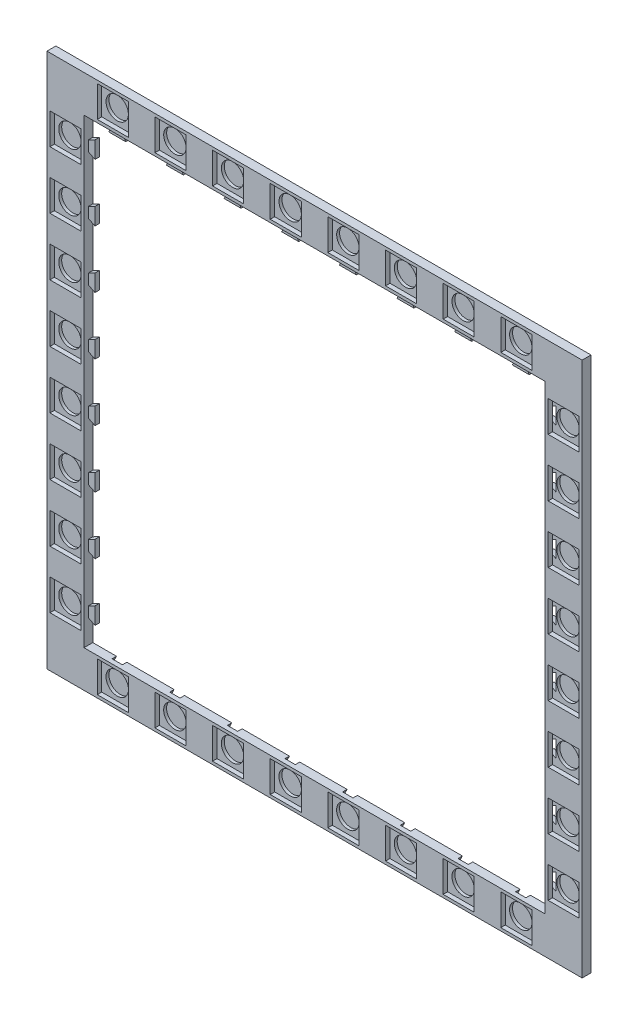
SolidWorks part; units mm, degrees
ref_plane "Front Plane" through (0, 0, 0) normal (1, 0, 0) x (0, 1, 0)
ref_plane "Top Plane" through (0, 0, 0) normal (0, 0, 1) x (0, 1, 0)
ref_plane "Right Plane" through (0, 0, 0) normal (0, 1, 0) x (-1, 0, 0)
sketch "Sketch1" plane through (0, 0, 0) normal (0, 0, 1) x (0, 1, 0)
  line L0 (150.3197, -166.5401) -> (150.3197, -150.5401)
  line L1 (150.3197, 12.4599) -> (150.3197, 44.4599)
  line L2 (154.7904, 81.2211) -> (154.7904, 92.6987)
  line L3 (150.3197, 129.4599) -> (150.3197, 145.4599)
  line L4 (150.3197, -111.5401) -> (154.7904, -113.7789)
  line L5 (154.7904, 14.6987) -> (150.3197, 12.4599)
  line L6 (154.7904, -102.3013) -> (150.3197, -104.5401)
  line L7 (150.3197, -72.5401) -> (154.7904, -74.7789)
  line L8 (150.3197, -150.5401) -> (154.7904, -152.7789)
  line L9 (150.3197, -65.5401) -> (150.3197, -33.5401)
  line L10 (154.7904, -141.3013) -> (150.3197, -143.5401)
  line L11 (154.7904, -35.7789) -> (154.7904, -24.3013)
  line L12 (154.7904, 42.2211) -> (154.7904, 53.6987)
  line L13 (150.3197, 83.4599) -> (154.7904, 81.2211)
  line L14 (154.7904, 3.2211) -> (154.7904, 14.6987)
  line L15 (154.7904, 131.6987) -> (150.3197, 129.4599)
  line L16 (150.3197, 5.4599) -> (154.7904, 3.2211)
  line L17 (150.3197, 122.4599) -> (154.7904, 120.2211)
  line L18 (154.7904, -113.7789) -> (154.7904, -102.3013)
  line L19 (154.7904, 53.6987) -> (150.3197, 51.4599)
  line L20 (150.3197, -104.5401) -> (150.3197, -72.5401)
  line L21 (154.7904, -24.3013) -> (150.3197, -26.5401)
  line L22 (150.3197, 90.4599) -> (150.3197, 122.4599)
  line L23 (154.7904, -63.3013) -> (150.3197, -65.5401)
  line L24 (154.7904, -152.7789) -> (154.7904, -141.3013)
  line L25 (150.3197, -33.5401) -> (154.7904, -35.7789)
  line L26 (154.7904, -74.7789) -> (154.7904, -63.3013)
  line L27 (150.3197, -26.5401) -> (150.3197, 5.4599)
  line L28 (150.3197, 44.4599) -> (154.7904, 42.2211)
  line L29 (154.7904, 120.2211) -> (154.7904, 131.6987)
  line L30 (150.3197, -143.5401) -> (150.3197, -111.5401)
  line L31 (150.3197, 51.4599) -> (150.3197, 83.4599)
  line L32 (154.7904, 92.6987) -> (150.3197, 90.4599)
  line L33 (-161.6803, -150.5401) -> (-157.2096, -152.7789)
  line L34 (-157.2096, -102.3013) -> (-161.6803, -104.5401)
  line L35 (-161.6803, -166.5401) -> (-161.6803, -150.5401)
  line L36 (-157.2096, -35.7789) -> (-157.2096, -24.3013)
  line L37 (-161.6803, 51.4599) -> (-161.6803, 83.4599)
  line L38 (-157.2096, -24.3013) -> (-161.6803, -26.5401)
  line L39 (-157.2096, 42.2211) -> (-157.2096, 53.6987)
  line L40 (-157.2096, 120.2211) -> (-157.2096, 131.6987)
  line L41 (-161.6803, 90.4599) -> (-161.6803, 122.4599)
  line L42 (-157.2096, -141.3013) -> (-161.6803, -143.5401)
  line L43 (-161.6803, 5.4599) -> (-157.2096, 3.2211)
  line L44 (-157.2096, -113.7789) -> (-157.2096, -102.3013)
  line L45 (-157.2096, -74.7789) -> (-157.2096, -63.3013)
  line L46 (-157.2096, 14.6987) -> (-161.6803, 12.4599)
  line L47 (-161.6803, -65.5401) -> (-161.6803, -33.5401)
  line L48 (-157.2096, 53.6987) -> (-161.6803, 51.4599)
  line L49 (-157.2096, 81.2211) -> (-157.2096, 92.6987)
  line L50 (-157.2096, -152.7789) -> (-157.2096, -141.3013)
  line L51 (-161.6803, -111.5401) -> (-157.2096, -113.7789)
  line L52 (-161.6803, -33.5401) -> (-157.2096, -35.7789)
  line L53 (-161.6803, 129.4599) -> (-161.6803, 145.4599)
  line L54 (-161.6803, -26.5401) -> (-161.6803, 5.4599)
  line L55 (-161.6803, 122.4599) -> (-157.2096, 120.2211)
  line L56 (-161.6803, -104.5401) -> (-161.6803, -72.5401)
  line L57 (-161.6803, 83.4599) -> (-157.2096, 81.2211)
  line L58 (-157.2096, 92.6987) -> (-161.6803, 90.4599)
  line L59 (-157.2096, 131.6987) -> (-161.6803, 129.4599)
  line L60 (-161.6803, 12.4599) -> (-161.6803, 44.4599)
  line L61 (-161.6803, -143.5401) -> (-161.6803, -111.5401)
  line L62 (-161.6803, -72.5401) -> (-157.2096, -74.7789)
  line L63 (-157.2096, 3.2211) -> (-157.2096, 14.6987)
  line L64 (-157.2096, -63.3013) -> (-161.6803, -65.5401)
  line L65 (-161.6803, 44.4599) -> (-157.2096, 42.2211)
  line L66 (-67.6803, 145.4599) -> (-99.6803, 145.4599)
  line L67 (-136.4415, 149.9306) -> (-147.9191, 149.9306)
  line L68 (136.5585, 149.9306) -> (125.0809, 149.9306)
  line L69 (-60.6803, 145.4599) -> (-58.4415, 149.9306)
  line L70 (-97.4415, 149.9306) -> (-108.9191, 149.9306)
  line L71 (86.0809, 149.9306) -> (88.3197, 145.4599)
  line L72 (127.3197, 145.4599) -> (95.3197, 145.4599)
  line L73 (49.3197, 145.4599) -> (17.3197, 145.4599)
  line L74 (-99.6803, 145.4599) -> (-97.4415, 149.9306)
  line L75 (150.3197, 145.4599) -> (134.3197, 145.4599)
  line L76 (-19.4415, 149.9306) -> (-30.9191, 149.9306)
  line L77 (134.3197, 145.4599) -> (136.5585, 149.9306)
  line L78 (8.0809, 149.9306) -> (10.3197, 145.4599)
  line L79 (-30.9191, 149.9306) -> (-28.6803, 145.4599)
  line L80 (10.3197, 145.4599) -> (-21.6803, 145.4599)
  line L81 (-58.4415, 149.9306) -> (-69.9191, 149.9306)
  line L82 (17.3197, 145.4599) -> (19.5585, 149.9306)
  line L83 (-108.9191, 149.9306) -> (-106.6803, 145.4599)
  line L84 (97.5585, 149.9306) -> (86.0809, 149.9306)
  line L85 (-21.6803, 145.4599) -> (-19.4415, 149.9306)
  line L86 (-106.6803, 145.4599) -> (-138.6803, 145.4599)
  line L87 (-145.6803, 145.4599) -> (-161.6803, 145.4599)
  line L88 (88.3197, 145.4599) -> (56.3197, 145.4599)
  line L89 (58.5585, 149.9306) -> (47.0809, 149.9306)
  line L90 (56.3197, 145.4599) -> (58.5585, 149.9306)
  line L91 (19.5585, 149.9306) -> (8.0809, 149.9306)
  line L92 (-69.9191, 149.9306) -> (-67.6803, 145.4599)
  line L93 (125.0809, 149.9306) -> (127.3197, 145.4599)
  line L94 (-138.6803, 145.4599) -> (-136.4415, 149.9306)
  line L95 (47.0809, 149.9306) -> (49.3197, 145.4599)
  line L96 (95.3197, 145.4599) -> (97.5585, 149.9306)
  line L97 (-28.6803, 145.4599) -> (-60.6803, 145.4599)
  line L98 (-147.9191, 149.9306) -> (-145.6803, 145.4599)
  line L99 (-30.9191, -162.0694) -> (-28.6803, -166.5401)
  line L100 (56.3197, -166.5401) -> (58.5585, -162.0694)
  line L101 (-28.6803, -166.5401) -> (-60.6803, -166.5401)
  line L102 (-99.6803, -166.5401) -> (-97.4415, -162.0694)
  line L103 (-21.6803, -166.5401) -> (-19.4415, -162.0694)
  line L104 (136.5585, -162.0694) -> (125.0809, -162.0694)
  line L105 (47.0809, -162.0694) -> (49.3197, -166.5401)
  line L106 (-106.6803, -166.5401) -> (-138.6803, -166.5401)
  line L107 (150.3197, -166.5401) -> (134.3197, -166.5401)
  line L108 (95.3197, -166.5401) -> (97.5585, -162.0694)
  line L109 (88.3197, -166.5401) -> (56.3197, -166.5401)
  line L110 (-147.9191, -162.0694) -> (-145.6803, -166.5401)
  line L111 (97.5585, -162.0694) -> (86.0809, -162.0694)
  line L112 (-69.9191, -162.0694) -> (-67.6803, -166.5401)
  line L113 (-145.6803, -166.5401) -> (-161.6803, -166.5401)
  line L114 (86.0809, -162.0694) -> (88.3197, -166.5401)
  line L115 (49.3197, -166.5401) -> (17.3197, -166.5401)
  line L116 (-97.4415, -162.0694) -> (-108.9191, -162.0694)
  line L117 (-138.6803, -166.5401) -> (-136.4415, -162.0694)
  line L118 (134.3197, -166.5401) -> (136.5585, -162.0694)
  line L119 (8.0809, -162.0694) -> (10.3197, -166.5401)
  line L120 (58.5585, -162.0694) -> (47.0809, -162.0694)
  line L121 (-60.6803, -166.5401) -> (-58.4415, -162.0694)
  line L122 (17.3197, -166.5401) -> (19.5585, -162.0694)
  line L123 (-19.4415, -162.0694) -> (-30.9191, -162.0694)
  line L124 (-108.9191, -162.0694) -> (-106.6803, -166.5401)
  line L125 (125.0809, -162.0694) -> (127.3197, -166.5401)
  line L126 (-67.6803, -166.5401) -> (-99.6803, -166.5401)
  line L127 (127.3197, -166.5401) -> (95.3197, -166.5401)
  line L128 (-136.4415, -162.0694) -> (-147.9191, -162.0694)
  line L129 (-58.4415, -162.0694) -> (-69.9191, -162.0694)
  line L130 (19.5585, -162.0694) -> (8.0809, -162.0694)
  line L131 (10.3197, -166.5401) -> (-21.6803, -166.5401)
  line L133 (-186.6803, 170.4599) -> (175.3197, 170.4599)
  line L134 (-186.6803, 170.4599) -> (-186.6803, -191.5401)
  line L135 (-186.6803, -191.5401) -> (175.3197, -191.5401)
  line L136 (175.3197, 170.4599) -> (175.3197, -191.5401)
  dimension "D1" = 312
  dimension "D2" = 312
  dimension "D3" = 312
  dimension "D4" = 312
  dimension "D5" = 25
  dimension "D6" = 25
  dimension "D7" = 25
  dimension "D8" = 25
  dimension "D9" = 25
extrude "Boss-Extrude1" add sketch "Sketch1" along normal blind 3 contours L134 L135 L136 L133
sketch "Sketch2" plane through (0, 0, 0) normal (0, 0, -1) x (1, 0, 0)
  line L0 (166.5401, -150.3197) -> (166.5401, -134.3197)
  line L1 (166.5401, 28.6803) -> (166.5401, 60.6803)
  line L2 (171.0109, 97.4415) -> (171.0109, 108.9191)
  line L3 (166.5401, 145.6803) -> (166.5401, 161.6803)
  line L4 (166.5401, -95.3197) -> (171.0109, -97.5585)
  line L5 (171.0109, 30.9191) -> (166.5401, 28.6803)
  line L6 (171.0109, -86.0809) -> (166.5401, -88.3197)
  line L7 (166.5401, -56.3197) -> (171.0109, -58.5585)
  line L8 (166.5401, -134.3197) -> (171.0109, -136.5585)
  line L9 (166.5401, -49.3197) -> (166.5401, -17.3197)
  line L10 (171.0109, -125.0809) -> (166.5401, -127.3197)
  line L11 (171.0109, -19.5585) -> (171.0109, -8.0809)
  line L12 (171.0109, 58.4415) -> (171.0109, 69.9191)
  line L13 (166.5401, 99.6803) -> (171.0109, 97.4415)
  line L14 (171.0109, 19.4415) -> (171.0109, 30.9191)
  line L15 (171.0109, 147.9191) -> (166.5401, 145.6803)
  line L16 (166.5401, 21.6803) -> (171.0109, 19.4415)
  line L17 (166.5401, 138.6803) -> (171.0109, 136.4415)
  line L18 (171.0109, -97.5585) -> (171.0109, -86.0809)
  line L19 (171.0109, 69.9191) -> (166.5401, 67.6803)
  line L20 (166.5401, -88.3197) -> (166.5401, -56.3197)
  line L21 (171.0109, -8.0809) -> (166.5401, -10.3197)
  line L22 (166.5401, 106.6803) -> (166.5401, 138.6803)
  line L23 (171.0109, -47.0809) -> (166.5401, -49.3197)
  line L24 (171.0109, -136.5585) -> (171.0109, -125.0809)
  line L25 (166.5401, -17.3197) -> (171.0109, -19.5585)
  line L26 (171.0109, -58.5585) -> (171.0109, -47.0809)
  line L27 (166.5401, -10.3197) -> (166.5401, 21.6803)
  line L28 (166.5401, 60.6803) -> (171.0109, 58.4415)
  line L29 (171.0109, 136.4415) -> (171.0109, 147.9191)
  line L30 (166.5401, -127.3197) -> (166.5401, -95.3197)
  line L31 (166.5401, 67.6803) -> (166.5401, 99.6803)
  line L32 (171.0109, 108.9191) -> (166.5401, 106.6803)
  line L33 (-145.4599, -134.3197) -> (-140.9891, -136.5585)
  line L34 (-140.9891, -86.0809) -> (-145.4599, -88.3197)
  line L35 (-145.4599, -150.3197) -> (-145.4599, -134.3197)
  line L36 (-140.9891, -19.5585) -> (-140.9891, -8.0809)
  line L37 (-145.4599, 67.6803) -> (-145.4599, 99.6803)
  line L38 (-140.9891, -8.0809) -> (-145.4599, -10.3197)
  line L39 (-140.9891, 58.4415) -> (-140.9891, 69.9191)
  line L40 (-140.9891, 136.4415) -> (-140.9891, 147.9191)
  line L41 (-145.4599, 106.6803) -> (-145.4599, 138.6803)
  line L42 (-140.9891, -125.0809) -> (-145.4599, -127.3197)
  line L43 (-145.4599, 21.6803) -> (-140.9891, 19.4415)
  line L44 (-140.9891, -97.5585) -> (-140.9891, -86.0809)
  line L45 (-140.9891, -58.5585) -> (-140.9891, -47.0809)
  line L46 (-140.9891, 30.9191) -> (-145.4599, 28.6803)
  line L47 (-145.4599, -49.3197) -> (-145.4599, -17.3197)
  line L48 (-140.9891, 69.9191) -> (-145.4599, 67.6803)
  line L49 (-140.9891, 97.4415) -> (-140.9891, 108.9191)
  line L50 (-140.9891, -136.5585) -> (-140.9891, -125.0809)
  line L51 (-145.4599, -95.3197) -> (-140.9891, -97.5585)
  line L52 (-145.4599, -17.3197) -> (-140.9891, -19.5585)
  line L53 (-145.4599, 145.6803) -> (-145.4599, 161.6803)
  line L54 (-145.4599, -10.3197) -> (-145.4599, 21.6803)
  line L55 (-145.4599, 138.6803) -> (-140.9891, 136.4415)
  line L56 (-145.4599, -88.3197) -> (-145.4599, -56.3197)
  line L57 (-145.4599, 99.6803) -> (-140.9891, 97.4415)
  line L58 (-140.9891, 108.9191) -> (-145.4599, 106.6803)
  line L59 (-140.9891, 147.9191) -> (-145.4599, 145.6803)
  line L60 (-145.4599, 28.6803) -> (-145.4599, 60.6803)
  line L61 (-145.4599, -127.3197) -> (-145.4599, -95.3197)
  line L62 (-145.4599, -56.3197) -> (-140.9891, -58.5585)
  line L63 (-140.9891, 19.4415) -> (-140.9891, 30.9191)
  line L64 (-140.9891, -47.0809) -> (-145.4599, -49.3197)
  line L65 (-145.4599, 60.6803) -> (-140.9891, 58.4415)
  line L66 (-51.4599, 161.6803) -> (-83.4599, 161.6803)
  line L67 (-120.2211, 166.1511) -> (-131.6987, 166.1511)
  line L68 (152.7789, 166.1511) -> (141.3013, 166.1511)
  line L69 (-44.4599, 161.6803) -> (-42.2211, 166.1511)
  line L70 (-81.2211, 166.1511) -> (-92.6987, 166.1511)
  line L71 (102.3013, 166.1511) -> (104.5401, 161.6803)
  line L72 (143.5401, 161.6803) -> (111.5401, 161.6803)
  line L73 (65.5401, 161.6803) -> (33.5401, 161.6803)
  line L74 (-83.4599, 161.6803) -> (-81.2211, 166.1511)
  line L75 (166.5401, 161.6803) -> (150.5401, 161.6803)
  line L76 (-3.2211, 166.1511) -> (-14.6987, 166.1511)
  line L77 (150.5401, 161.6803) -> (152.7789, 166.1511)
  line L78 (24.3013, 166.1511) -> (26.5401, 161.6803)
  line L79 (-14.6987, 166.1511) -> (-12.4599, 161.6803)
  line L80 (26.5401, 161.6803) -> (-5.4599, 161.6803)
  line L81 (-42.2211, 166.1511) -> (-53.6987, 166.1511)
  line L82 (33.5401, 161.6803) -> (35.7789, 166.1511)
  line L83 (-92.6987, 166.1511) -> (-90.4599, 161.6803)
  line L84 (113.7789, 166.1511) -> (102.3013, 166.1511)
  line L85 (-5.4599, 161.6803) -> (-3.2211, 166.1511)
  line L86 (-90.4599, 161.6803) -> (-122.4599, 161.6803)
  line L87 (-129.4599, 161.6803) -> (-145.4599, 161.6803)
  line L88 (104.5401, 161.6803) -> (72.5401, 161.6803)
  line L89 (74.7789, 166.1511) -> (63.3013, 166.1511)
  line L90 (72.5401, 161.6803) -> (74.7789, 166.1511)
  line L91 (35.7789, 166.1511) -> (24.3013, 166.1511)
  line L92 (-53.6987, 166.1511) -> (-51.4599, 161.6803)
  line L93 (141.3013, 166.1511) -> (143.5401, 161.6803)
  line L94 (-122.4599, 161.6803) -> (-120.2211, 166.1511)
  line L95 (63.3013, 166.1511) -> (65.5401, 161.6803)
  line L96 (111.5401, 161.6803) -> (113.7789, 166.1511)
  line L97 (-12.4599, 161.6803) -> (-44.4599, 161.6803)
  line L98 (-131.6987, 166.1511) -> (-129.4599, 161.6803)
  line L99 (-14.6987, -145.8489) -> (-12.4599, -150.3197)
  line L100 (72.5401, -150.3197) -> (74.7789, -145.8489)
  line L101 (-12.4599, -150.3197) -> (-44.4599, -150.3197)
  line L102 (-83.4599, -150.3197) -> (-81.2211, -145.8489)
  line L103 (-5.4599, -150.3197) -> (-3.2211, -145.8489)
  line L104 (152.7789, -145.8489) -> (141.3013, -145.8489)
  line L105 (63.3013, -145.8489) -> (65.5401, -150.3197)
  line L106 (-90.4599, -150.3197) -> (-122.4599, -150.3197)
  line L107 (166.5401, -150.3197) -> (150.5401, -150.3197)
  line L108 (111.5401, -150.3197) -> (113.7789, -145.8489)
  line L109 (104.5401, -150.3197) -> (72.5401, -150.3197)
  line L110 (-131.6987, -145.8489) -> (-129.4599, -150.3197)
  line L111 (113.7789, -145.8489) -> (102.3013, -145.8489)
  line L112 (-53.6987, -145.8489) -> (-51.4599, -150.3197)
  line L113 (-129.4599, -150.3197) -> (-145.4599, -150.3197)
  line L114 (102.3013, -145.8489) -> (104.5401, -150.3197)
  line L115 (65.5401, -150.3197) -> (33.5401, -150.3197)
  line L116 (-81.2211, -145.8489) -> (-92.6987, -145.8489)
  line L117 (-122.4599, -150.3197) -> (-120.2211, -145.8489)
  line L118 (150.5401, -150.3197) -> (152.7789, -145.8489)
  line L119 (24.3013, -145.8489) -> (26.5401, -150.3197)
  line L120 (74.7789, -145.8489) -> (63.3013, -145.8489)
  line L121 (-44.4599, -150.3197) -> (-42.2211, -145.8489)
  line L122 (33.5401, -150.3197) -> (35.7789, -145.8489)
  line L123 (-3.2211, -145.8489) -> (-14.6987, -145.8489)
  line L124 (-92.6987, -145.8489) -> (-90.4599, -150.3197)
  line L125 (141.3013, -145.8489) -> (143.5401, -150.3197)
  line L126 (-51.4599, -150.3197) -> (-83.4599, -150.3197)
  line L127 (143.5401, -150.3197) -> (111.5401, -150.3197)
  line L128 (-120.2211, -145.8489) -> (-131.6987, -145.8489)
  line L129 (-42.2211, -145.8489) -> (-53.6987, -145.8489)
  line L130 (35.7789, -145.8489) -> (24.3013, -145.8489)
  line L131 (26.5401, -150.3197) -> (-5.4599, -150.3197)
  line L132 (-170.4599, 186.6803) -> (-170.4599, -175.3197) construction
  line L133 (-170.4599, 186.6803) -> (191.5401, 186.6803) construction
  dimension "D1" = 25
  dimension "D2" = 25
extrude "Cut-Extrude3" cut sketch "Sketch2" against normal blind 3 contours L31 L13 L2 L32 L22 L17 L29 L15 L3 L75 L77 L68 L93 L72 L96 L84 L71 L88 L90 L89 L95 L73 L82 L91 L78 L80 L85 L76 L79 L97 L69 L81 L92 L66 L74 L70 L83 L86 L94 L67 L98 L87 L53 L59 L40 L55 L41 L58 L49 L57 L37 L48 L39 L65 L60 L46 L63 L43 L54 L38 L36 L52 L47 L64 L45 L62 L56 L34 L44 L51 L61 L42 L50 L33 L35 L113 L110 L128 L117 L106 L124 L116 L102 L126 L112 L129 L121 L101 L99 L123 L103 L131 L119 L130 L122 L115 L105 L120 L100 L109 L114 L111 L108 L127 L125 L104 L118 L107 L0 L8 L24 L10 L30 L4 L18 L6 L20 L7 L26 L23 L9 L25 L11 L21 L27 L16 L14 L5 L1 L28 L12 L19
sketch "Sketch3" plane through (0, 0, 3) normal (0, 0, 1) x (1, 0, 0)
  line L0 (-170.4599, 175.3197) -> (191.5401, 175.3197)
  line L1 (191.5401, 175.3197) -> (191.5401, -186.6803)
  line L2 (191.5401, -186.6803) -> (-170.4599, -186.6803)
  line L3 (-170.4599, -186.6803) -> (-170.4599, 175.3197)
  line L4 (-145.4599, 150.3197) -> (166.5401, 150.3197)
  line L5 (166.5401, 150.3197) -> (166.5401, -161.6803)
  line L6 (166.5401, -161.6803) -> (-145.4599, -161.6803)
  line L7 (-145.4599, -161.6803) -> (-145.4599, 150.3197)
extrude "Boss-Extrude3" add sketch "Sketch3" along normal blind 3
sketch "Sketch4" plane through (0, 0, 6) normal (0, 0, 1) x (1, 0, 0)
  line L0 (-170.4599, 175.3197) -> (-170.4599, -186.6803) construction
  line L1 (-147.4599, -131.6803) -> (-168.4599, -131.6803)
  line L2 (-147.4599, -131.6803) -> (-147.4599, -152.6803)
  line L3 (-147.4599, -152.6803) -> (-168.4599, -152.6803)
  line L4 (-168.4599, -131.6803) -> (-168.4599, -152.6803)
  line L5 (-147.4599, -92.6803) -> (-147.4599, -113.6803)
  line L6 (-147.4599, -92.6803) -> (-168.4599, -92.6803)
  line L7 (-145.4599, 150.3197) -> (-145.4599, -161.6803) construction
  line L8 (-168.4599, -92.6803) -> (-168.4599, -113.6803)
  line L9 (-147.4599, -113.6803) -> (-168.4599, -113.6803)
  line L10 (-147.4599, -53.6803) -> (-147.4599, -74.6803)
  line L11 (-147.4599, -53.6803) -> (-168.4599, -53.6803)
  line L12 (-168.4599, -53.6803) -> (-168.4599, -74.6803)
  line L13 (-147.4599, -74.6803) -> (-168.4599, -74.6803)
  line L14 (-147.4599, -14.6803) -> (-147.4599, -35.6803)
  line L15 (-147.4599, -14.6803) -> (-168.4599, -14.6803)
  line L16 (-168.4599, -14.6803) -> (-168.4599, -35.6803)
  line L17 (-147.4599, -35.6803) -> (-168.4599, -35.6803)
  line L18 (-147.4599, 24.3197) -> (-147.4599, 3.3197)
  line L19 (-147.4599, 24.3197) -> (-168.4599, 24.3197)
  line L20 (-168.4599, 24.3197) -> (-168.4599, 3.3197)
  line L21 (-147.4599, 3.3197) -> (-168.4599, 3.3197)
  line L22 (-147.4599, 63.3197) -> (-147.4599, 42.3197)
  line L23 (-147.4599, 63.3197) -> (-168.4599, 63.3197)
  line L24 (-168.4599, 63.3197) -> (-168.4599, 42.3197)
  line L25 (-147.4599, 42.3197) -> (-168.4599, 42.3197)
  line L26 (-147.4599, 102.3197) -> (-147.4599, 81.3197)
  line L27 (-147.4599, 102.3197) -> (-168.4599, 102.3197)
  line L28 (-168.4599, 102.3197) -> (-168.4599, 81.3197)
  line L29 (-147.4599, 81.3197) -> (-168.4599, 81.3197)
  line L30 (-147.4599, 141.3197) -> (-147.4599, 120.3197)
  line L31 (-147.4599, 141.3197) -> (-168.4599, 141.3197)
  line L32 (-168.4599, 141.3197) -> (-168.4599, 120.3197)
  line L33 (-147.4599, 120.3197) -> (-168.4599, 120.3197)
  line L37 (189.5401, -152.6803) -> (168.5401, -152.6803)
  line L38 (189.5401, -74.6803) -> (168.5401, -74.6803)
  line L39 (189.5401, 63.3197) -> (189.5401, 42.3197)
  line L40 (168.5401, -131.6803) -> (168.5401, -152.6803)
  line L41 (189.5401, -53.6803) -> (189.5401, -74.6803)
  line L42 (189.5401, -14.6803) -> (168.5401, -14.6803)
  line L43 (189.5401, 24.3197) -> (189.5401, 3.3197)
  line L44 (189.5401, 3.3197) -> (168.5401, 3.3197)
  line L45 (189.5401, 24.3197) -> (168.5401, 24.3197)
  line L46 (189.5401, -113.6803) -> (168.5401, -113.6803)
  line L47 (189.5401, 102.3197) -> (189.5401, 81.3197)
  line L48 (189.5401, -35.6803) -> (168.5401, -35.6803)
  line L49 (189.5401, 141.3197) -> (189.5401, 120.3197)
  line L50 (189.5401, 141.3197) -> (168.5401, 141.3197)
  line L51 (168.5401, 141.3197) -> (168.5401, 120.3197)
  line L52 (189.5401, -131.6803) -> (168.5401, -131.6803)
  line L53 (168.5401, -92.6803) -> (168.5401, -113.6803)
  line L54 (189.5401, 120.3197) -> (168.5401, 120.3197)
  line L55 (189.5401, -14.6803) -> (189.5401, -35.6803)
  line L56 (168.5401, 63.3197) -> (168.5401, 42.3197)
  line L57 (189.5401, -92.6803) -> (189.5401, -113.6803)
  line L58 (168.5401, -14.6803) -> (168.5401, -35.6803)
  line L59 (189.5401, 42.3197) -> (168.5401, 42.3197)
  line L60 (189.5401, -92.6803) -> (168.5401, -92.6803)
  line L61 (189.5401, 63.3197) -> (168.5401, 63.3197)
  line L62 (189.5401, 102.3197) -> (168.5401, 102.3197)
  line L63 (189.5401, -131.6803) -> (189.5401, -152.6803)
  line L64 (189.5401, -53.6803) -> (168.5401, -53.6803)
  line L65 (168.5401, 102.3197) -> (168.5401, 81.3197)
  line L67 (189.5401, 81.3197) -> (168.5401, 81.3197)
  line L68 (168.5401, -53.6803) -> (168.5401, -74.6803)
  line L69 (168.5401, 24.3197) -> (168.5401, 3.3197)
  dimension "D1" = 2
  dimension "D2" = 8
  dimension "D4" = 2
sketch "Sketch5" plane through (0, 0, 6) normal (0, 0, 1) x (1, 0, 0)
  line L0 (-136.4599, 173.3197) -> (-136.4599, 152.3197)
  line L1 (-136.4599, 152.3197) -> (-115.4599, 152.3197)
  line L2 (-115.4599, 152.3197) -> (-115.4599, 173.3197)
  line L3 (-115.4599, 173.3197) -> (-136.4599, 173.3197)
  line L4 (-125.9599, 173.3197) -> (-125.9599, 152.3197) construction
  line L5 (191.5401, 175.3197) -> (-170.4599, 175.3197) construction
  line L6 (-97.4599, 173.3197) -> (-97.4599, 152.3197)
  line L7 (-125.9599, 145.8489) -> (-125.9599, 175.3197) construction
  line L8 (-120.2211, 145.8489) -> (-131.6987, 145.8489) construction
  line L9 (-97.4599, 152.3197) -> (-76.4599, 152.3197)
  line L10 (-76.4599, 152.3197) -> (-76.4599, 173.3197)
  line L11 (-58.4599, 173.3197) -> (-58.4599, 152.3197)
  line L12 (-58.4599, 152.3197) -> (-37.4599, 152.3197)
  line L13 (-37.4599, 152.3197) -> (-37.4599, 173.3197)
  line L14 (-19.4599, 173.3197) -> (-19.4599, 152.3197)
  line L15 (-19.4599, 152.3197) -> (1.5401, 152.3197)
  line L16 (1.5401, 152.3197) -> (1.5401, 173.3197)
  line L17 (19.5401, 173.3197) -> (19.5401, 152.3197)
  line L18 (19.5401, 152.3197) -> (40.5401, 152.3197)
  line L19 (40.5401, 152.3197) -> (40.5401, 173.3197)
  line L20 (58.5401, 173.3197) -> (58.5401, 152.3197)
  line L21 (58.5401, 152.3197) -> (79.5401, 152.3197)
  line L22 (79.5401, 152.3197) -> (79.5401, 173.3197)
  line L23 (97.5401, 173.3197) -> (97.5401, 152.3197)
  line L24 (97.5401, 152.3197) -> (118.5401, 152.3197)
  line L25 (118.5401, 152.3197) -> (118.5401, 173.3197)
  line L26 (136.5401, 173.3197) -> (136.5401, 152.3197)
  line L27 (136.5401, 152.3197) -> (157.5401, 152.3197)
  line L28 (157.5401, 152.3197) -> (157.5401, 173.3197)
  line L29 (-76.4599, 173.3197) -> (-97.4599, 173.3197)
  line L30 (-37.4599, 173.3197) -> (-58.4599, 173.3197)
  line L31 (1.5401, 173.3197) -> (-19.4599, 173.3197)
  line L32 (19.5401, 173.3197) -> (40.5401, 173.3197)
  line L33 (58.5401, 173.3197) -> (79.5401, 173.3197)
  line L34 (97.5401, 173.3197) -> (118.5401, 173.3197)
  line L35 (136.5401, 173.3197) -> (157.5401, 173.3197)
  line L42 (58.5401, -163.6803) -> (58.5401, -184.6803)
  line L44 (157.5401, -184.6803) -> (157.5401, -163.6803)
  line L45 (-97.4599, -163.6803) -> (-97.4599, -184.6803)
  line L46 (58.5401, -163.6803) -> (79.5401, -163.6803)
  line L47 (-136.4599, -184.6803) -> (-115.4599, -184.6803)
  line L48 (-19.4599, -184.6803) -> (1.5401, -184.6803)
  line L49 (97.5401, -163.6803) -> (118.5401, -163.6803)
  line L50 (-97.4599, -184.6803) -> (-76.4599, -184.6803)
  line L51 (19.5401, -184.6803) -> (40.5401, -184.6803)
  line L52 (-19.4599, -163.6803) -> (-19.4599, -184.6803)
  line L53 (-37.4599, -163.6803) -> (-58.4599, -163.6803)
  line L54 (136.5401, -163.6803) -> (157.5401, -163.6803)
  line L55 (40.5401, -184.6803) -> (40.5401, -163.6803)
  line L56 (97.5401, -163.6803) -> (97.5401, -184.6803)
  line L57 (136.5401, -163.6803) -> (136.5401, -184.6803)
  line L58 (1.5401, -163.6803) -> (-19.4599, -163.6803)
  line L59 (-115.4599, -163.6803) -> (-136.4599, -163.6803)
  line L60 (1.5401, -184.6803) -> (1.5401, -163.6803)
  line L61 (118.5401, -184.6803) -> (118.5401, -163.6803)
  line L63 (79.5401, -184.6803) -> (79.5401, -163.6803)
  line L65 (-136.4599, -163.6803) -> (-136.4599, -184.6803)
  line L66 (-76.4599, -184.6803) -> (-76.4599, -163.6803)
  line L68 (-115.4599, -184.6803) -> (-115.4599, -163.6803)
  line L69 (-58.4599, -184.6803) -> (-37.4599, -184.6803)
  line L70 (19.5401, -163.6803) -> (19.5401, -184.6803)
  line L71 (-76.4599, -163.6803) -> (-97.4599, -163.6803)
  line L72 (-58.4599, -163.6803) -> (-58.4599, -184.6803)
  line L73 (-37.4599, -184.6803) -> (-37.4599, -163.6803)
  line L75 (58.5401, -184.6803) -> (79.5401, -184.6803)
  line L76 (97.5401, -184.6803) -> (118.5401, -184.6803)
  line L77 (136.5401, -184.6803) -> (157.5401, -184.6803)
  line L78 (19.5401, -163.6803) -> (40.5401, -163.6803)
  dimension "D1" = 2
  dimension "D2" = 21
  dimension "D3" = 21
  dimension "D4" = 8
  dimension "D7" = 21
  dimension "D8" = 21
extrude "Cut-Extrude4" cut sketch "Sketch4" against normal blind 3
extrude "Cut-Extrude5" cut sketch "Sketch5" against normal blind 3
sketch "Sketch6" plane through (0, 0, 3) normal (0, 0, 1) x (1, 0, 0)
  line L0 (-168.4599, 141.3197) -> (-147.4599, 120.3197) construction
  line L1 (-147.4599, 120.3197) -> (-147.4599, 141.3197) construction
  line L2 (-147.4599, 141.3197) -> (-168.4599, 120.3197) construction
  line L3 (-136.4599, 152.3197) -> (-115.4599, 173.3197) construction
  line L4 (168.5401, 120.3197) -> (189.5401, 141.3197) construction
  line L5 (-136.4599, -184.6803) -> (-115.4599, -163.6803) construction
  circle A0 centre (-157.9599, 130.8197) radius 7.56
  circle A1 centre (-125.9599, -174.1803) radius 7.6
  circle A2 centre (179.0401, 130.8197) radius 7.6
  circle A3 centre (-125.9599, 162.8197) radius 7.56
  circle A4 centre (-86.9599, 162.8197) radius 7.56
  circle A5 centre (-47.9599, 162.8197) radius 7.56
  circle A6 centre (-8.9599, 162.8197) radius 7.56
  circle A7 centre (30.0401, 162.8197) radius 7.56
  circle A8 centre (69.0401, 162.8197) radius 7.56
  circle A9 centre (108.0401, 162.8197) radius 7.56
  circle A10 centre (147.0401, 162.8197) radius 7.56
  circle A11 centre (-157.9599, 91.8197) radius 7.56
  circle A12 centre (-157.9599, 52.8197) radius 7.56
  circle A13 centre (-157.9599, 13.8197) radius 7.56
  circle A14 centre (-157.9599, -25.1803) radius 7.56
  circle A15 centre (-157.9599, -64.1803) radius 7.56
  circle A16 centre (-157.9599, -103.1803) radius 7.56
  circle A17 centre (-157.9599, -142.1803) radius 7.56
  circle A18 centre (-86.9599, -174.1803) radius 7.6
  circle A19 centre (-47.9599, -174.1803) radius 7.6
  circle A20 centre (-8.9599, -174.1803) radius 7.6
  circle A21 centre (30.0401, -174.1803) radius 7.6
  circle A22 centre (69.0401, -174.1803) radius 7.6
  circle A23 centre (108.0401, -174.1803) radius 7.6
  circle A24 centre (147.0401, -174.1803) radius 7.6
  circle A25 centre (179.0401, 91.8197) radius 7.6
  circle A26 centre (179.0401, 52.8197) radius 7.6
  circle A27 centre (179.0401, 13.8197) radius 7.6
  circle A28 centre (179.0401, -25.1803) radius 7.6
  circle A29 centre (179.0401, -64.1803) radius 7.6
  circle A30 centre (179.0401, -103.1803) radius 7.6
  circle A31 centre (179.0401, -142.1803) radius 7.6
  dimension "D1" = 15.12
  dimension "D2" = 15.2
  dimension "D3" = 15.2
  dimension "D4" = 15.12
  dimension "D5" = 8
  dimension "D6" = 8
  dimension "D7" = 8
  dimension "D8" = 8
extrude "Cut-Extrude6" cut sketch "Sketch6" against normal blind 2
